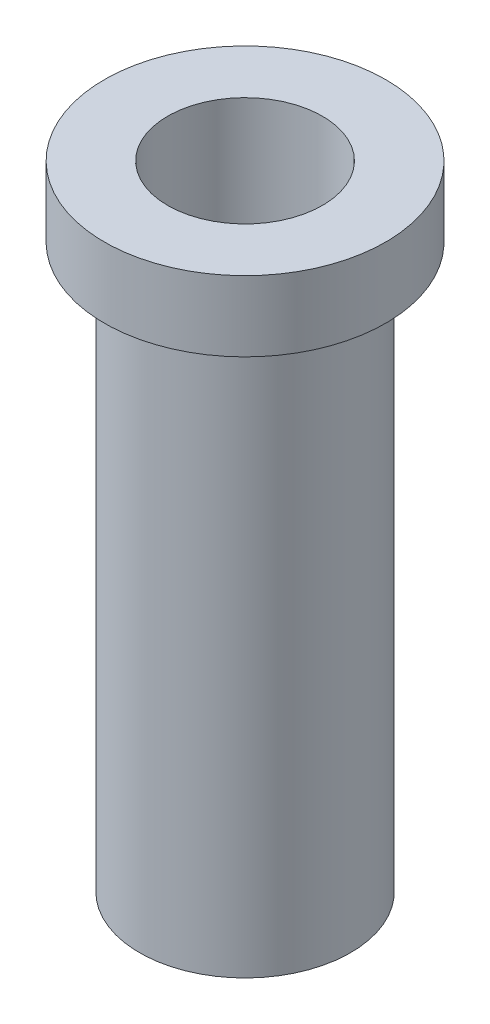
SolidWorks part; units mm, degrees
ref_plane "Front Plane" through (0, 0, 0) normal (0, 0, 1) x (1, 0, 0)
ref_plane "Top Plane" through (0, 0, 0) normal (0, 1, 0) x (1, 0, 0)
ref_plane "Right Plane" through (0, 0, 0) normal (1, 0, 0) x (0, 0, -1)
sketch "Sketch1" plane through (0, 0, 0) normal (0, 0, 1) x (1, 0, 0)
  line L0 (0, 0) -> (0, 45)
  line L1 (0, 45) -> (10, 45)
  line L2 (10, 45) -> (10, 40)
  line L3 (10, 40) -> (7.5, 40)
  line L4 (7.5, 40) -> (7.5, 0)
  line L5 (7.5, 0) -> (0, 0)
  dimension "D1" = 5
  dimension "D2" = 45
  dimension "D3" = 10
  dimension "D4" = 7.5
revolve "Revolve1" add sketch "Sketch1" angle 360 about L0
sketch "Sketch2" plane through (0, 45, 0) normal (0, 1, 0) x (1, 0, 0)
  circle A0 centre (0, 0) radius 5.5
  dimension "D1" = 11
extrude "Cut-Extrude1" cut sketch "Sketch2" against normal through all
